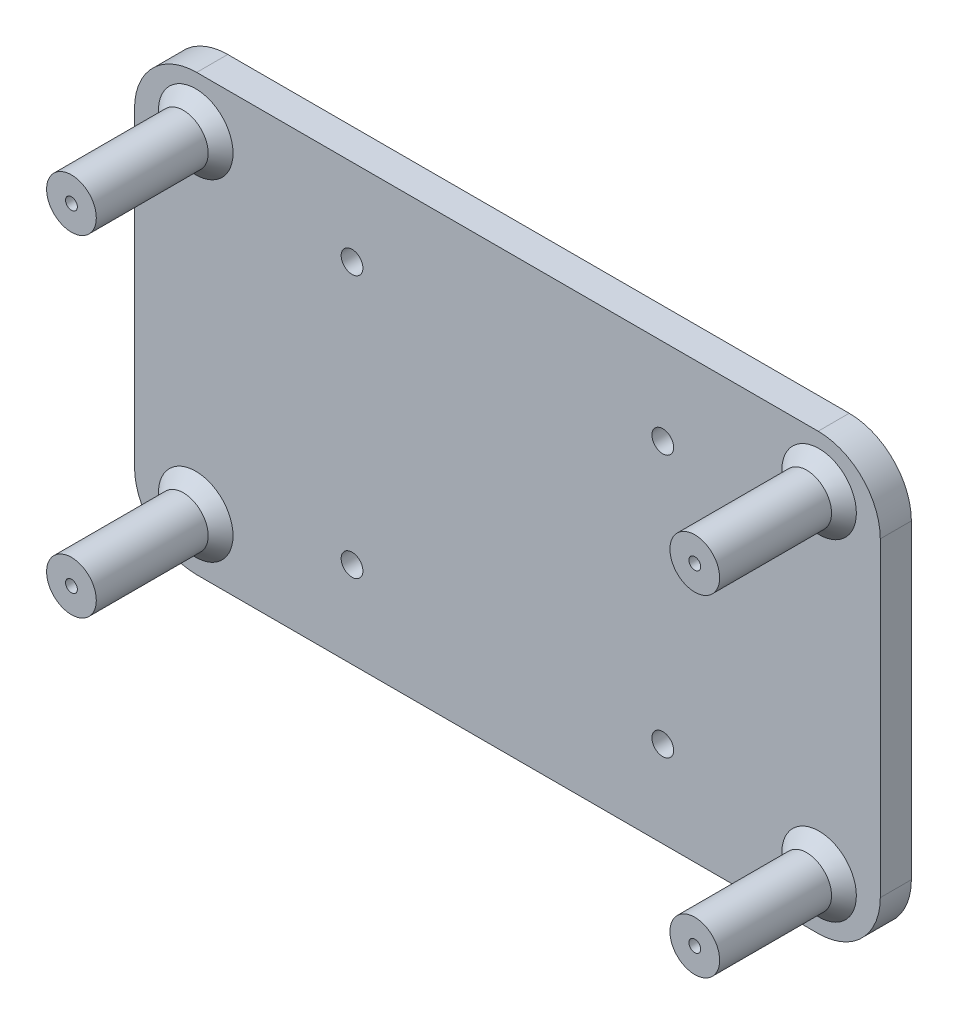
SolidWorks part; units mm, degrees
ref_plane "Piano frontale" through (0, 0, 0) normal (0, 0, 1) x (1, 0, 0)
ref_plane "Piano superiore" through (0, 0, 0) normal (0, 1, 0) x (1, 0, 0)
ref_plane "Piano destro" through (0, 0, 0) normal (1, 0, 0) x (0, 0, -1)
sketch "Schizzo1" plane through (0, 0, 0) normal (0, 0, 1) x (1, 0, 0)
  line L1 (60, -35) -> (-60, -35)
  line L2 (60, -35) -> (60, 35)
  line L3 (60, 35) -> (-60, 35)
  line L4 (-60, -35) -> (-60, 35)
  line L5 (60, -35) -> (-60, 35) construction
  line L6 (60, 35) -> (-60, -35) construction
  point P0 (0, 0)
  dimension "D1" = 120
  dimension "D2" = 70
extrude "Estrusione-Estrusione1" add sketch "Schizzo1" along normal blind 5
sketch "Schizzo2" plane through (0, 0, 5) normal (0, 0, 1) x (1, 0, 0)
  line L1 (50.15, -26.65) -> (-50.15, -26.65) construction
  line L2 (50.15, -26.65) -> (50.15, 26.65) construction
  line L3 (50.15, 26.65) -> (-50.15, 26.65) construction
  line L4 (-50.15, -26.65) -> (-50.15, 26.65) construction
  line L5 (50.15, -26.65) -> (-50.15, 26.65) construction
  line L6 (50.15, 26.65) -> (-50.15, -26.65) construction
  circle A0 centre (-50.15, 26.65) radius 4
  circle A1 centre (50.15, -26.65) radius 4
  circle A2 centre (50.15, 26.65) radius 4
  circle A3 centre (-50.15, -26.65) radius 4
  point P0 (0, 0)
  dimension "D3" = 8
  dimension "D1" = 100.3
  dimension "D2" = 53.3
extrude "Estrusione-Estrusione2" add sketch "Schizzo2" along normal blind 20
chamfer "Smusso1" distance 2 angle 45 4 edges at (54.15, 26.65, 5) (54.15, -26.65, 5) (-46.15, -26.65, 5) (-46.15, 26.65, 5)
sketch "Schizzo3" plane through (0, 0, 25) normal (0, 0, 1) x (1, 0, 0)
  circle A0 centre (-50.15, 26.65) radius 0.95
  circle A1 centre (50.15, 26.65) radius 0.95
  circle A2 centre (50.15, -26.65) radius 0.95
  circle A3 centre (-50.15, -26.65) radius 0.95
  dimension "D1" = 1.9
extrude "Taglio-Estrusione1" cut sketch "Schizzo3" against normal blind 15
fillet "Raccordo1" radius 10 4 edges at (60, -35, 2.5) (60, 35, 2.5) (-60, 35, 2.5) (-60, -35, 2.5)
sketch "Schizzo4" plane through (0, 0, 5) normal (0, 0, 1) x (1, 0, 0)
  line L1 (25, -21.1017) -> (-25, -21.1017) construction
  line L2 (25, -21.1017) -> (25, 21.1017) construction
  line L3 (25, 21.1017) -> (-25, 21.1017) construction
  line L4 (-25, -21.1017) -> (-25, 21.1017) construction
  line L5 (25, -21.1017) -> (-25, 21.1017) construction
  line L6 (25, 21.1017) -> (-25, -21.1017) construction
  circle A0 centre (-25, 21.1017) radius 1.75
  circle A1 centre (25, 21.1017) radius 1.75
  circle A2 centre (25, -21.1017) radius 1.75
  circle A3 centre (-25, -21.1017) radius 1.75
  point P0 (0, 0)
  dimension "D3" = 3.5
  dimension "D1" = 42.2034
  dimension "D2" = 50
extrude "Taglio-Estrusione2" cut sketch "Schizzo4" against normal blind 10
